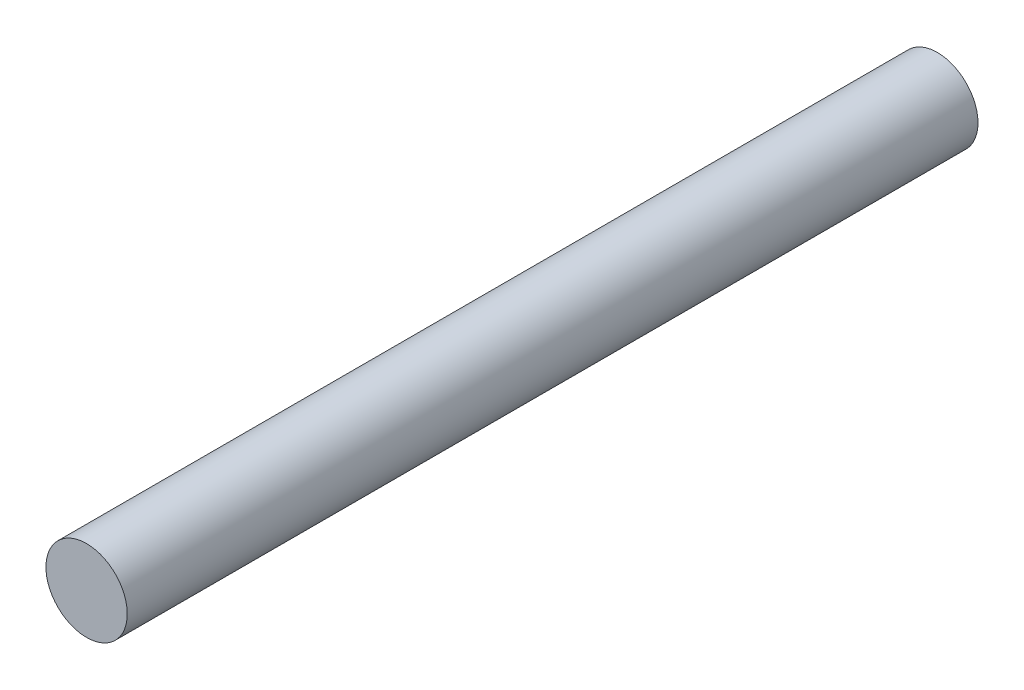
SolidWorks part; units mm, degrees
ref_plane "Front Plane" through (0, 0, 0) normal (0, 0, 1) x (1, 0, 0)
ref_plane "Top Plane" through (0, 0, 0) normal (0, 1, 0) x (1, 0, 0)
ref_plane "Right Plane" through (0, 0, 0) normal (1, 0, 0) x (0, 0, -1)
sketch "Sketch1" plane through (0, 0, 0) normal (0, 0, 1) x (1, 0, 0)
  circle A0 centre (0, 0) radius 2.5
  dimension "D1" = 5
extrude "Boss-Extrude1" add sketch "Sketch1" along normal blind 52.3
